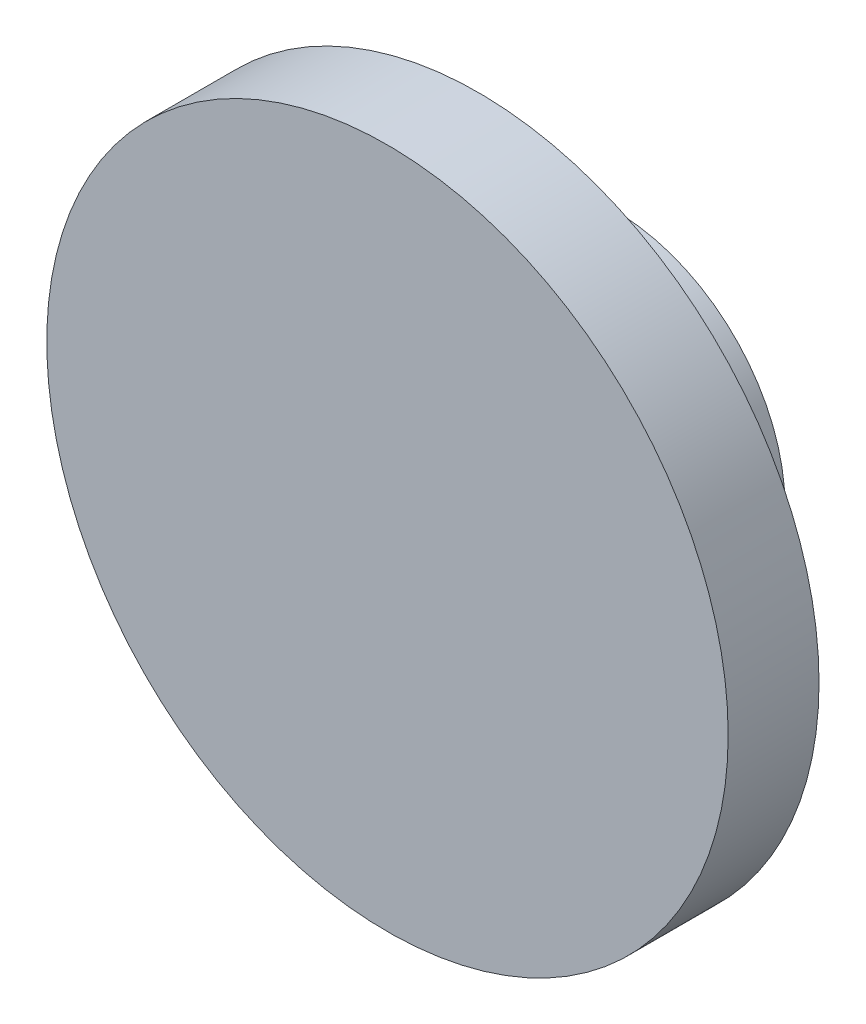
SolidWorks part; units mm, degrees
ref_plane "Front Plane" through (0, 0, 0) normal (0, 0, 1) x (1, 0, 0)
ref_plane "Top Plane" through (0, 0, 0) normal (0, 1, 0) x (1, 0, 0)
ref_plane "Right Plane" through (0, 0, 0) normal (1, 0, 0) x (0, 0, -1)
sketch "Sketch1" plane through (0, 0, 0) normal (0, 0, 1) x (1, 0, 0)
  circle A0 centre (0, 0) radius 15
  dimension "D1" = 30
extrude "Boss-Extrude2" add sketch "Sketch1" along normal blind 4
sketch "Sketch2" plane through (0, 0, 0) normal (0, 0, -1) x (-1, 0, 0)
  circle A0 centre (0, 0) radius 7.5
  dimension "D1" = 15
extrude "Boss-Extrude3" add sketch "Sketch2" along normal blind 6
sketch "Sketch3" plane through (0, 0, -6) normal (0, 0, -1) x (-1, 0, 0)
  circle A0 centre (0, 0) radius 4
  dimension "D1" = 8
extrude "Cut-Extrude1" cut sketch "Sketch3" against normal blind 2
sketch "Sketch4" plane through (0, 0, -4) normal (0, 0, -1) x (-1, 0, 0)
  line L0 (0, 0) -> (0, 11.0996) construction
  line L1 (0, 0) -> (0, -6.5542) construction
  line L2 (0, 0) -> (0, 4)
  line L3 (0, 4) -> (0, -4)
  circle A0 centre (0, 0) radius 4 construction
  arc A1 (0, 4) -> (0, -4) centre (0, 0) cw
sketch "Sketch5" plane through (0, 0, 0) normal (1, 0, 0) x (0, 0, -1)
  line L0 (4, 6.5) -> (4, -6.5)
  line L1 (6, 7.5) -> (4, 6.5) construction
  line L2 (6, 7.5) -> (4, 7.5) construction
  line L3 (4, 7.5) -> (4, 6.5) construction
  line L4 (6, -7.5) -> (4, -6.5) construction
  line L5 (6, -7.5) -> (4, -7.5) construction
  line L7 (4, -7.5) -> (4, -6.5) construction
  line L8 (4, 6.5) -> (4, -6.5) construction
  line L10 (4, 6.5) -> (4, -6.5)
  arc A0 (4, 6.5) -> (4, -6.5) centre (4, 0) ccw
  dimension "D3" = 6.5
  dimension "D1" = 1
  dimension "D2" = 2
  dimension "D4" = 1
revolve "Cut-Revolve2" cut sketch "Sketch5" angle 360 about L0
